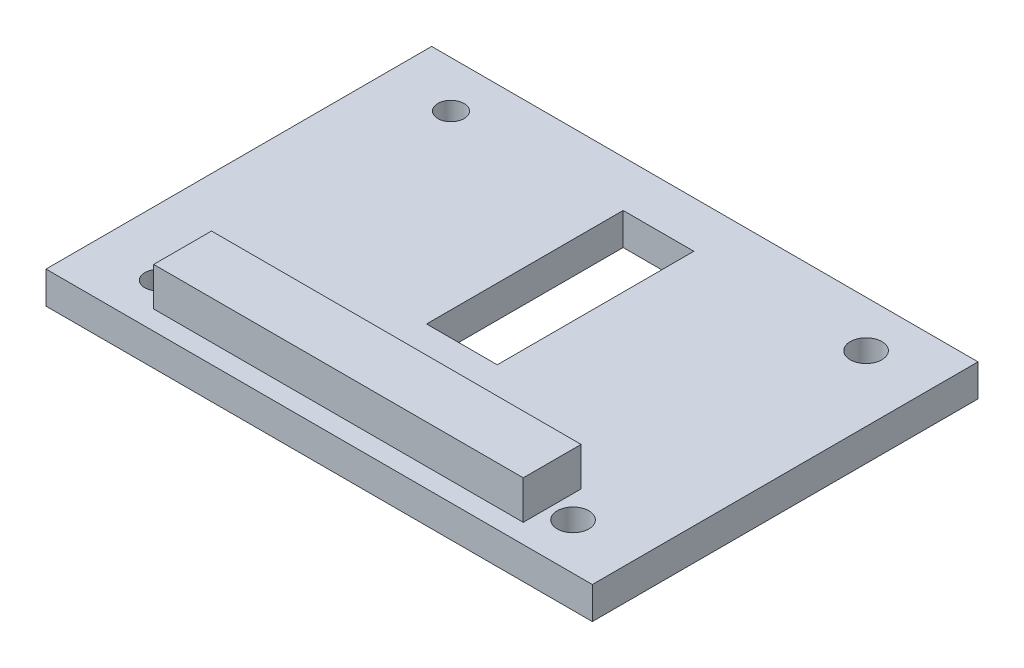
SolidWorks part; units mm, degrees
ref_plane "前视基准面" through (0, 0, 0) normal (0, 0, 1) x (1, 0, 0)
ref_plane "上视基准面" through (0, 0, 0) normal (0, 1, 0) x (1, 0, 0)
ref_plane "右视基准面" through (0, 0, 0) normal (1, 0, 0) x (0, 0, -1)
other "Configuration Table"
sketch "01_Base_Profile" plane through (0, 0, 0) normal (0, 1, 0) x (1, 0, 0)
  line L1 (-85, -60) -> (85, -60)
  line L2 (-85, -60) -> (-85, 60)
  line L3 (-85, 60) -> (85, 60)
  line L4 (85, -60) -> (85, 60)
  line L5 (-85, -60) -> (85, 60) construction
  line L6 (-85, 60) -> (85, -60) construction
  line L7 (-11, -15.5889) -> (11, -15.5889)
  line L8 (-11, -15.5889) -> (-11, 45.5889)
  line L9 (-11, 45.5889) -> (11, 45.5889)
  line L10 (11, -15.5889) -> (11, 45.5889)
  line L11 (-11, -15.5889) -> (11, 45.5889) construction
  line L12 (-11, 45.5889) -> (11, -15.5889) construction
  circle A0 centre (-64.5843, -45.5889) radius 4.0843
  circle A1 centre (64.5843, -45.5889) radius 4.9157
  circle A2 centre (-64.5843, 45.5889) radius 4.0843
  circle A3 centre (64.5843, 45.5889) radius 4.9157
  point P0 (0, 0)
  point P14 (0, 15)
extrude "01_Base_Extrude" add sketch "01_Base_Profile" along normal blind 10
sketch "02_Boss_Profile" plane through (0, 0, 0) normal (0, 1, 0) x (1, 0, 0)
  line L1 (-57.5, -54) -> (57.5, -54)
  line L2 (-57.5, -54) -> (-57.5, -36)
  line L3 (-57.5, -36) -> (57.5, -36)
  line L4 (57.5, -54) -> (57.5, -36)
  line L5 (-57.5, -54) -> (57.5, -36) construction
  line L6 (-57.5, -36) -> (57.5, -54) construction
  point P0 (0, -45)
extrude "02_Reinforcement_Boss" add sketch "02_Boss_Profile" along normal blind 22
